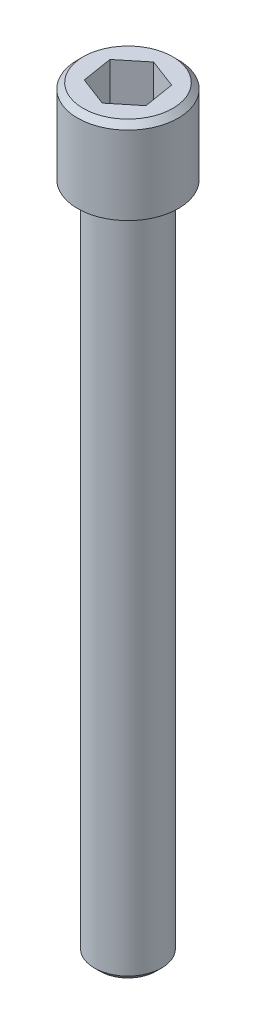
SolidWorks part; units mm, degrees
ref_plane "Přední rovina" through (0, 0, 0) normal (0, 0, 1) x (1, 0, 0)
ref_plane "Horní rovina" through (0, 0, 0) normal (0, 1, 0) x (1, 0, 0)
ref_plane "Pravá rovina" through (0, 0, 0) normal (1, 0, 0) x (0, 0, -1)
sketch "Skica1" plane through (0, 0, 0) normal (0, 1, 0) x (1, 0, 0)
  circle A0 centre (0, 0) radius 1.5
  dimension "D1" = 3
extrude "Přidat vysunutím1" add sketch "Skica1" along normal blind 30
sketch "Skica2" plane through (0, 30, 0) normal (0, 1, 0) x (1, 0, 0)
  circle A0 centre (0, 0) radius 2.25
  dimension "D1" = 4.5
extrude "Přidat vysunutím2" add sketch "Skica2" along normal blind 3.75
sketch "Skica3" plane through (0, 33.75, 0) normal (0, 1, 0) x (1, 0, 0)
  line L1 (-1.0744, -0.875) -> (0.2206, -1.368)
  line L2 (0.2206, -1.368) -> (1.295, -0.493)
  line L3 (1.295, -0.493) -> (1.0744, 0.875)
  line L4 (1.0744, 0.875) -> (-0.2206, 1.368)
  line L5 (-0.2206, 1.368) -> (-1.295, 0.493)
  line L6 (-1.295, 0.493) -> (-1.0744, -0.875)
  circle A0 centre (0, 0) radius 1.2 construction
  dimension "D1" = 2.4
extrude "Odebrat vysunutím1" cut sketch "Skica3" against normal blind 2.25
chamfer "Zkosení1" distance 0.25 angle 45 1 edges at (0, 33.75, 2.25)
chamfer "Zkosení2" distance 0.25 angle 45 1 edges at (0, 0, 1.5)
